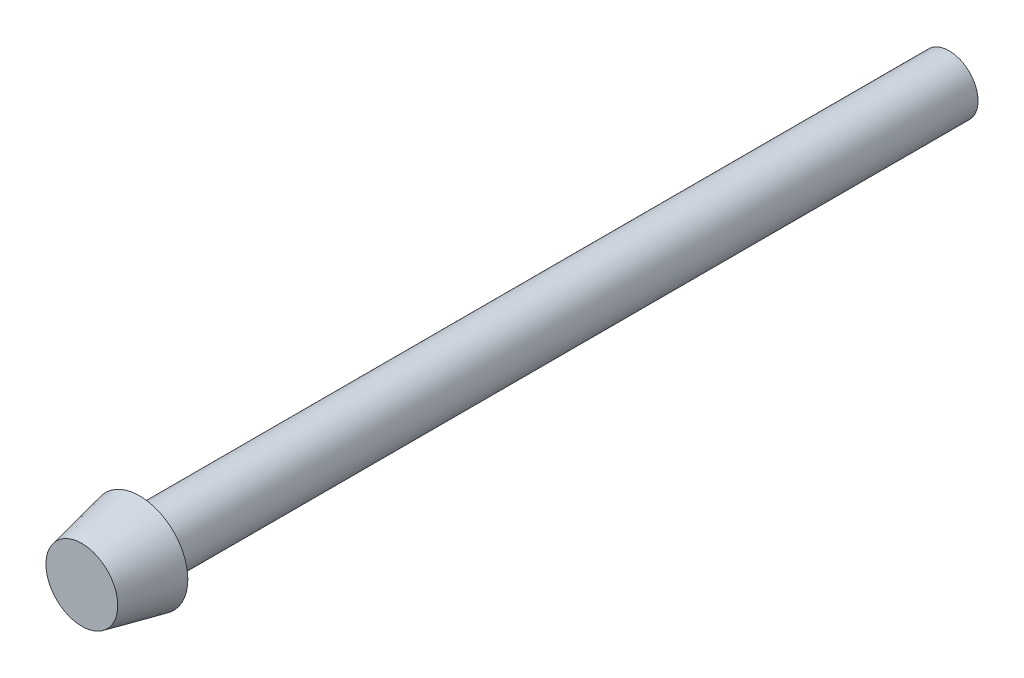
SolidWorks part; units mm, degrees
ref_plane "Plan de face" through (0, 0, 0) normal (0, 0, 1) x (1, 0, 0)
ref_plane "Plan de dessus" through (0, 0, 0) normal (0, 1, 0) x (1, 0, 0)
ref_plane "Plan de droite" through (0, 0, 0) normal (1, 0, 0) x (0, 0, -1)
sketch "Esquisse1" plane through (0, 0, 0) normal (0, 0, 1) x (1, 0, 0)
  circle A0 centre (0, 0) radius 1.5
  dimension "D1" = 3
extrude "Boss.-Extru.1" add sketch "Esquisse1" along normal blind 42
sketch "Esquisse2" plane through (0, 0, 42) normal (0, 0, 1) x (1, 0, 0)
  circle A0 centre (0, 0) radius 2.5
  dimension "D1" = 5
extrude "Boss.-Extru.2" add sketch "Esquisse2" along normal blind 3 draft 12
